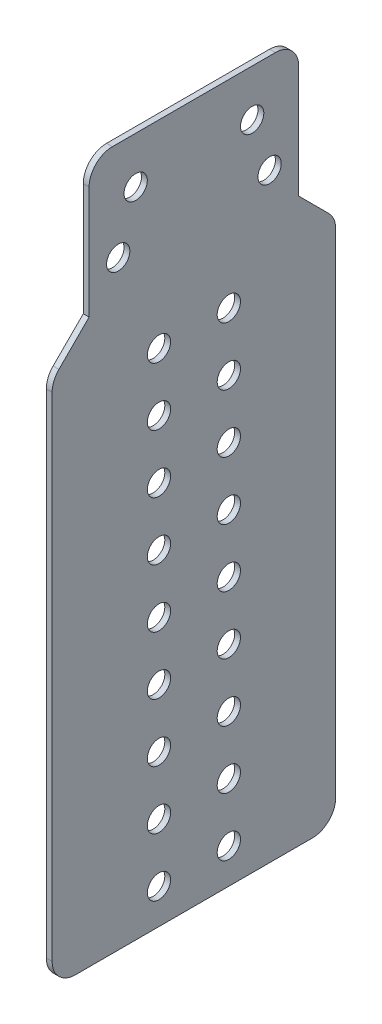
SolidWorks part; units mm, degrees
material "PVC 0.007 Plasticized"
ref_plane "Front Plane" through (0, 0, 0) normal (0, 0, 1) x (1, 0, 0)
ref_plane "Top Plane" through (0, 0, 0) normal (0, 1, 0) x (1, 0, 0)
ref_plane "Right Plane" through (0, 0, 0) normal (1, 0, 0) x (0, 0, -1)
sketch "Sketch1" plane through (0, 0, 0) normal (1, 0, 0) x (0, 0, -1)
  line L1 (-18, 0) -> (18, 0)
  line L2 (-18, 0) -> (-18, -120)
  line L3 (-18, -120) -> (18, -120)
  line L4 (18, 0) -> (18, -120)
  line L5 (-18, 0) -> (18, -120) construction
  line L6 (-18, -120) -> (18, 0) construction
  point P4 (0, -60)
  point P5 (0, 0)
  dimension "D1" = 120
  dimension "D2" = 36
extrude "Boss-Extrude1" add sketch "Sketch1" along normal blind 1 contours L2 L3 L4 L1
hole_wizard "Ø4.0 (4) Diameter Hole2" positions "Sketch2" profile "Sketch3" hole size "Ø4.0" standard "ISO" end condition through all
sketch "Sketch2" plane through (0, 0, 0) normal (-1, 0, 0) x (0, 0, 1)
  line L0 (18, 0) -> (-18, 0) construction
  line L1 (18, 0) -> (18, -120) construction
  line L2 (-18, 0) -> (-18, -120) construction
  point P0 (-10, -8)
  point P3 (10, -8)
  dimension "D1" = 8
  dimension "D2" = 8
  dimension "D3" = 8
  dimension "D4" = 8
sketch "Sketch3" plane through (0, -8, -10) normal (0, 1, 0) x (0, 0, 1)
  line L0 (0, 0) -> (0, 1)
  line L1 (0, 1) -> (2, 1)
  line L2 (2, 1) -> (2, 0)
  line L5 (2, 0) -> (0, 0)
  line L11 (0, -6.35) -> (0, 107.95) construction
  dimension "Thru Hole Dia." = 4
  dimension "Thru Hole Depth" = 1
hole_wizard "Ø4.0 (4) Diameter Hole3" positions "Sketch4" profile "Sketch5" hole size "Ø4.0" standard "ISO" end condition through all
sketch "Sketch4" plane through (0, 0, 0) normal (-1, 0, 0) x (0, 0, 1)
  line L0 (-18, 0) -> (-18, -120) construction
  line L1 (18, 0) -> (18, -120) construction
  line L2 (18, 0) -> (-18, 0) construction
  point P0 (-13, -17)
  point P3 (13, -17)
  dimension "D1" = 5
  dimension "D2" = 5
  dimension "D3" = 17
  dimension "D4" = 17
sketch "Sketch5" plane through (0, -17, -13) normal (0, 1, 0) x (0, 0, 1)
  line L0 (0, 0) -> (0, 1)
  line L1 (0, 1) -> (2, 1)
  line L2 (2, 1) -> (2, 0)
  line L5 (2, 0) -> (0, 0)
  line L11 (0, -6.35) -> (0, 107.95) construction
  dimension "Thru Hole Dia." = 4
  dimension "Thru Hole Depth" = 1
sketch "Sketch6" plane through (1, 0, 0) normal (1, 0, 0) x (0, 0, -1)
  line L0 (-18, -120) -> (18, -120) construction
  point P0 (-6, -114)
  point P1 (6, -114)
  dimension "D1" = 12
  dimension "D2" = 6
  dimension "D3" = 6
hole_wizard "Ø4.0 (4) Diameter Hole1" positions "Sketch7" profile "Sketch8" hole size "Ø4.0" standard "ISO" end condition through all
sketch "Sketch7" plane through (1, 0, 0) normal (1, 0, 0) x (0, 0, -1)
  point P0 (6, -114)
  point P3 (-6, -114)
  point P16 (6, -104)
  point P17 (-6, -104)
  point P18 (6, -94)
  point P19 (-6, -94)
  point P20 (6, -84)
  point P21 (-6, -84)
  point P22 (6, -74)
  point P23 (-6, -74)
  point P24 (6, -64)
  point P25 (-6, -64)
  point P26 (6, -54)
  point P27 (-6, -54)
  point P28 (6, -44)
  point P29 (-6, -44)
  point P30 (6, -34)
  point P31 (-6, -34)
  dimension "D1" = 9
sketch "Sketch8" plane through (1, -114, -6) normal (0, 1, 0) x (0, 0, -1)
  line L0 (0, 0) -> (0, 1)
  line L1 (0, 1) -> (2, 1)
  line L2 (2, 1) -> (2, 0)
  line L5 (2, 0) -> (0, 0)
  line L11 (0, -6.35) -> (0, 107.95) construction
  dimension "Thru Hole Dia." = 4
  dimension "Thru Hole Depth" = 1
sketch "Sketch9" plane through (0, 0, 0) normal (-1, 0, 0) x (0, 0, 1)
  line L0 (18, -23.35) -> (23.1784, -28.5284)
  line L1 (18, 0) -> (18, -120) construction
  line L2 (24.35, -31.3569) -> (24.35, -116)
  line L3 (20.35, -120) -> (18, -120)
  line L4 (18, -120) -> (18, -23.35)
  line L5 (-18, -23.35) -> (-23.1784, -28.5284)
  line L6 (-18, 0) -> (-18, -120) construction
  line L7 (-24.35, -31.3569) -> (-24.35, -116)
  line L8 (-20.35, -120) -> (-18, -120)
  line L9 (-18, -120) -> (-18, -23.35)
  circle A0 centre (13, -17) radius 2 construction
  circle A2 centre (-13, -17) radius 2 construction
  arc A3 (24.35, -116) -> (20.35, -120) centre (20.35, -116) cw
  arc A4 (-24.35, -116) -> (-20.35, -120) centre (-20.35, -116) ccw
  arc A5 (23.1784, -28.5284) -> (24.35, -31.3569) centre (20.35, -31.3569) cw
  arc A6 (-23.1784, -28.5284) -> (-24.35, -31.3569) centre (-20.35, -31.3569) ccw
  dimension "D2" = 6.35
  dimension "D5" = 6.35
  dimension "D7" = 4
  dimension "D1" = 6.35
  dimension "D3" = 45
  dimension "D4" = 6.35
  dimension "D6" = 45
extrude "Boss-Extrude2" add sketch "Sketch9" against normal up to surface (1 mm away) up to face at (1, -114, -8)
fillet "Fillet1" radius 4 2 edges at (0.5, 0, 18) (0.5, 0, -18)
